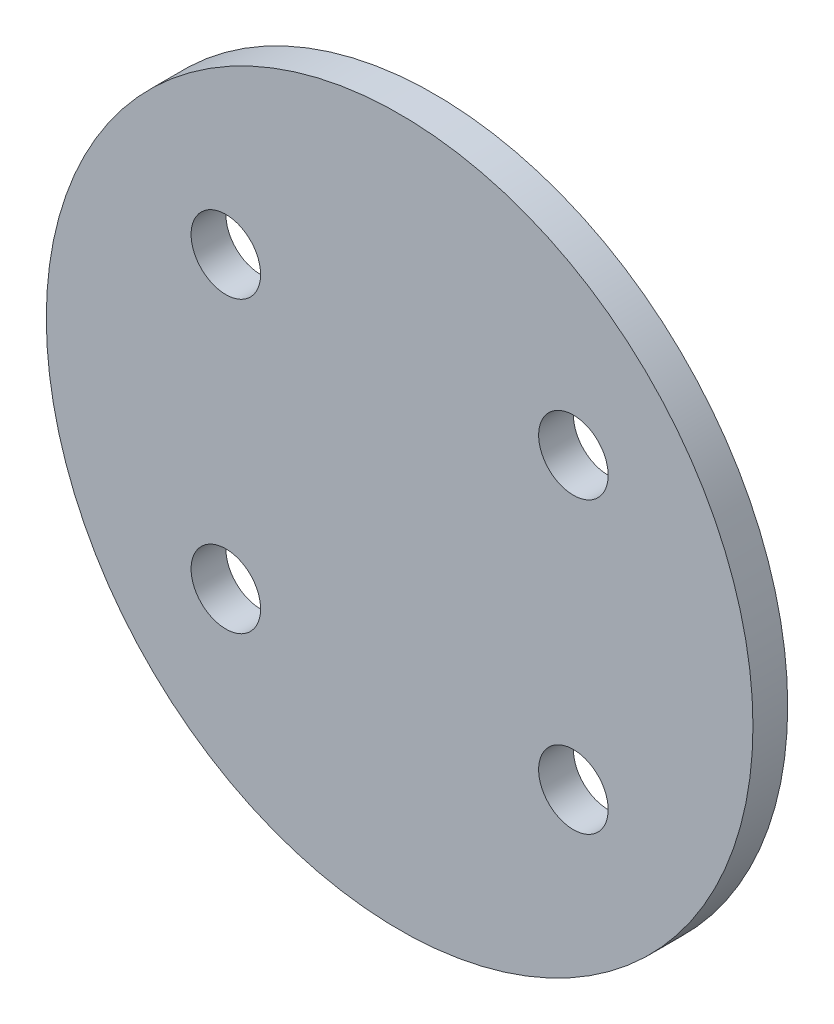
SolidWorks part; units mm, degrees
material "Acrylic (Medium-high impact)"
ref_plane "Front Plane" through (0, 0, 0) normal (0, 0, 1) x (1, 0, 0)
ref_plane "Top Plane" through (0, 0, 0) normal (0, 1, 0) x (1, 0, 0)
ref_plane "Right Plane" through (0, 0, 0) normal (1, 0, 0) x (0, 0, -1)
sketch "Model" plane through (0, 0, 0) normal (0, 0, 1) x (1, 0, 0)
  line L1 (15, -12.5) -> (-15, -12.5) construction
  line L2 (15, -12.5) -> (15, 12.5) construction
  line L3 (15, 12.5) -> (-15, 12.5) construction
  line L4 (-15, -12.5) -> (-15, 12.5) construction
  line L5 (15, -12.5) -> (-15, 12.5) construction
  line L6 (15, 12.5) -> (-15, -12.5) construction
  circle A0 centre (15, 12.5) radius 3
  circle A1 centre (15, -12.5) radius 3
  circle A2 centre (-15, -12.5) radius 3
  circle A5 centre (0, 0) radius 30.5
  circle A11 centre (-15, 12.5) radius 3
  dimension "D1" = 61
  dimension "D2" = 6
  dimension "D3" = 30
  dimension "D4" = 25
extrude "Boss-Extrude1" add sketch "Model" along normal blind 3
